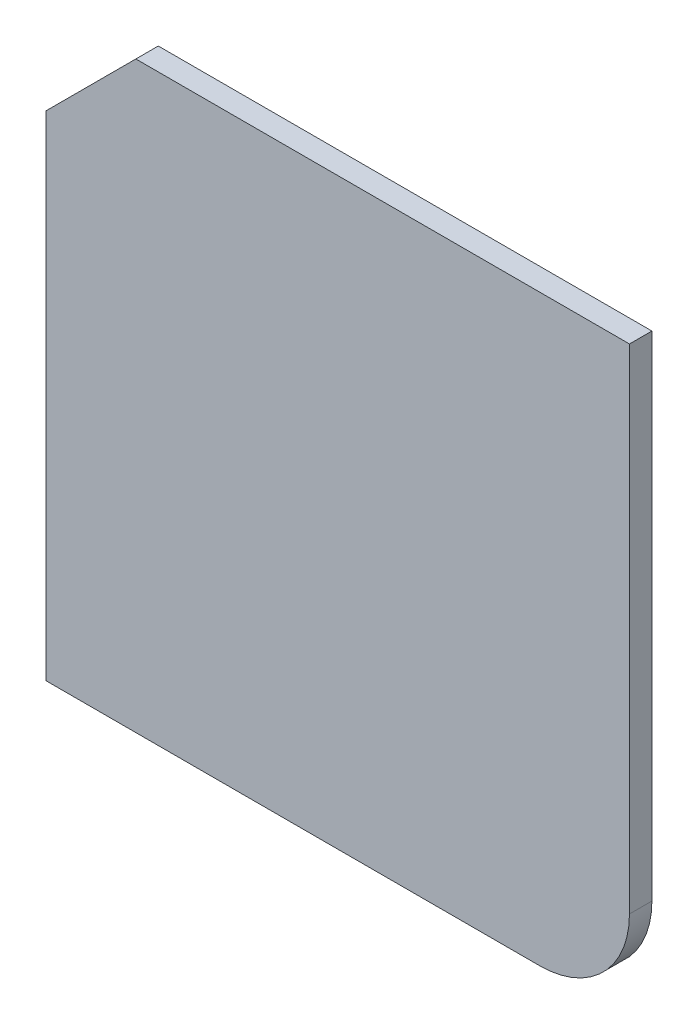
SolidWorks part; units mm, degrees
ref_plane "Front Plane" through (0, 0, 0) normal (0, 0, 1) x (1, 0, 0)
ref_plane "Top Plane" through (0, 0, 0) normal (0, 1, 0) x (1, 0, 0)
ref_plane "Right Plane" through (0, 0, 0) normal (1, 0, 0) x (0, 0, -1)
sketch "Sketch1" plane through (0, 0, 0) normal (0, 0, 1) x (1, 0, 0)
  line L1 (0, 0) -> (130, 0)
  line L2 (0, 0) -> (0, 130)
  line L3 (0, 130) -> (130, 130)
  line L4 (130, 0) -> (130, 130)
  dimension "D1" = 130
  dimension "D2" = 130
extrude "Boss-Extrude1" add sketch "Sketch1" along normal blind 5
fillet "Fillet1" radius 20 1 edges at (130, 0, 2.5)
chamfer "Chamfer1" distance 20 angle 45 1 edges at (0, 130, 2.5)
